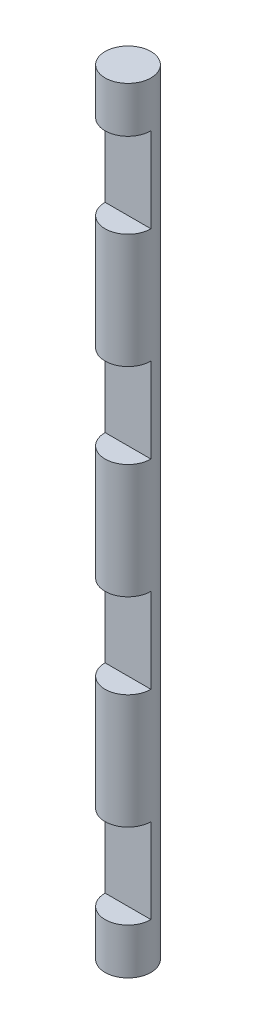
SolidWorks part; units mm, degrees
material "ABS"
ref_plane "Front Plane" through (0, 0, 0) normal (0, 0, 1) x (1, 0, 0)
ref_plane "Top Plane" through (0, 0, 0) normal (0, 1, 0) x (1, 0, 0)
ref_plane "Right Plane" through (0, 0, 0) normal (1, 0, 0) x (0, 0, -1)
sketch "Sketch1" plane through (0, 0, 0) normal (0, 1, 0) x (1, 0, 0)
  circle A0 centre (0, 0) radius 13
  dimension "D1" = 26
extrude "Boss-Extrude1" add sketch "Sketch1" along normal blind 1
ref_plane "Plane1" through (0, 1, 0) normal (0, 1, 0) x (1, 0, 0)
ref_plane "Plane2" through (0, 4.7, 0) normal (0, 1, 0) x (1, 0, 0)
ref_plane "Plane3" through (0, 9.7, 0) normal (0, 1, 0) x (1, 0, 0)
ref_plane "Plane4" through (0, 13.4, 0) normal (0, 1, 0) x (1, 0, 0)
ref_plane "Plane5" through (0, 18.4, 0) normal (0, 1, 0) x (1, 0, 0)
ref_plane "Plane6" through (0, 22.1, 0) normal (0, 1, 0) x (1, 0, 0)
ref_plane "Plane7" through (0, 27.1, 0) normal (0, 1, 0) x (1, 0, 0)
ref_plane "Plane8" through (0, 30.8, 0) normal (0, 1, 0) x (1, 0, 0)
sketch "Sketch16" plane through (0, 30.8, 0) normal (0, 1, 0) x (1, 0, 0)
  circle A0 centre (0, 0) radius 13
  circle A1 centre (0, 0) radius 13 construction
  dimension "D1" = 0
extrude "Boss-Extrude3" add sketch "Sketch16" along normal blind 1 separate body
sketch "Sketch18" plane through (0, 4.7, 0) normal (0, 1, 0) x (1, 0, 0)
  line L1 (-11, -11) -> (11, -11)
  line L2 (-11, -11) -> (-11, 11)
  line L3 (-11, 11) -> (11, 11)
  line L4 (11, -11) -> (11, 11)
  dimension "D1" = 22
  dimension "D2" = 22
  dimension "D3" = 11
  dimension "D4" = 11
sketch "Sketch19" plane through (0, 1, 0) normal (0, 1, 0) x (1, 0, 0)
  circle A0 centre (0, 11) radius 1
  point P13 (0, 0)
  dimension "D1" = 2
  dimension "D2" = 11
extrude "Boss-Extrude4" add sketch "Sketch19" along normal up to surface (29.8 mm away) up to face at (0, 30.8, 13)
extrude "Cut-Extrude6" cut sketch "Sketch18" against normal blind 3.7
sketch "Sketch21" plane through (0, 13.4, 0) normal (0, 1, 0) x (1, 0, 0)
  line L1 (-11, -11) -> (11, -11)
  line L2 (-11, -11) -> (-11, 11)
  line L3 (-11, 11) -> (11, 11)
  line L4 (11, -11) -> (11, 11)
  dimension "D1" = 22
  dimension "D2" = 22
  dimension "D3" = 11
  dimension "D4" = 11
extrude "Cut-Extrude7" cut sketch "Sketch21" against normal blind 3.7
sketch "Sketch22" plane through (0, 22.1, 0) normal (0, 1, 0) x (1, 0, 0)
  line L5 (-11, -11) -> (11, -11)
  line L6 (-11, -11) -> (-11, 11)
  line L7 (-11, 11) -> (11, 11)
  line L8 (11, -11) -> (11, 11)
  dimension "D1" = 11
  dimension "D2" = 11
  dimension "D3" = 22
  dimension "D4" = 22
extrude "Cut-Extrude8" cut sketch "Sketch22" against normal blind 3.7
sketch "Sketch23" plane through (0, 30.8, 0) normal (0, 1, 0) x (1, 0, 0)
  line L1 (-11, -11) -> (11, -11)
  line L2 (-11, -11) -> (-11, 11)
  line L3 (-11, 11) -> (11, 11)
  line L4 (11, -11) -> (11, 11)
  dimension "D1" = 22
  dimension "D2" = 22
  dimension "D3" = 11
  dimension "D4" = 11
extrude "Cut-Extrude9" cut sketch "Sketch23" against normal blind 3.7
sketch "Sketch24" plane through (0, 31.8, 0) normal (0, 1, 0) x (1, 0, 0)
  circle A0 centre (0, 0) radius 19.9218
extrude "Cut-Extrude10" cut sketch "Sketch24" against normal blind 1
sketch "Sketch25" plane through (0, 1, 0) normal (0, 1, 0) x (1, 0, 0)
  circle A0 centre (0, 0) radius 36.1829
extrude "Cut-Extrude11" cut sketch "Sketch25" against normal blind 1
sketch "Sketch26" plane through (0, 30.8, 0) normal (0, 1, 0) x (1, 0, 0)
  circle A0 centre (0, 11) radius 1
  arc A2 (1, 11) -> (-1, 11) centre (0, 11) ccw construction
  dimension "D1" = 0
  dimension "D2" = 2
extrude "Boss-Extrude5" add sketch "Sketch26" along normal blind 2
sketch "Sketch27" plane through (0, 1, 0) normal (0, -1, 0) x (1, 0, 0)
  circle A0 centre (0, -11) radius 1
extrude "Boss-Extrude6" add sketch "Sketch27" along normal blind 2
